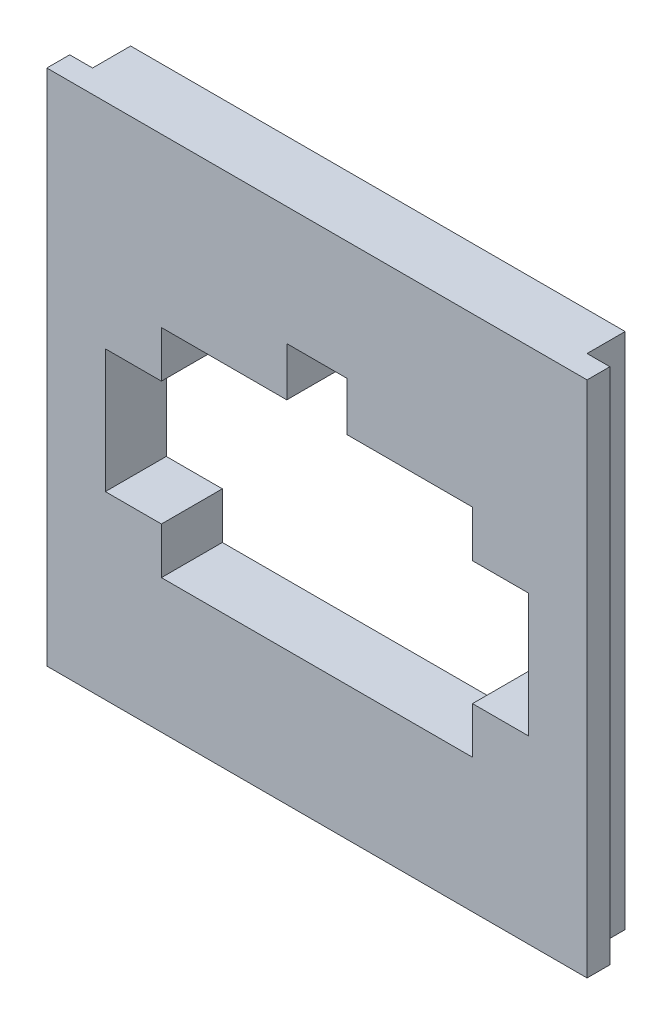
SolidWorks part; units mm, degrees
material "PET"
ref_plane "Front Plane" through (0, 0, 0) normal (0, 0, 1) x (1, 0, 0)
ref_plane "Top Plane" through (0, 0, 0) normal (0, 1, 0) x (1, 0, 0)
ref_plane "Right Plane" through (0, 0, 0) normal (1, 0, 0) x (0, 0, -1)
sketch "Sketch1" plane through (0, 0, 0) normal (0, 0, 1) x (1, 0, 0)
  line L1 (-5.7029, 6.1497) -> (10.5271, 6.1497)
  line L2 (-5.7029, 6.1497) -> (-5.7029, -10.8503)
  line L3 (-5.7029, -10.8503) -> (10.5271, -10.8503)
  line L4 (10.5271, 6.1497) -> (10.5271, -10.8503)
  dimension "D1" = 17
  dimension "D2" = 16.23
extrude "Boss-Extrude1" add sketch "Sketch1" along normal blind 2
sketch "Sketch2" plane through (10.5271, 0, 0) normal (1, 0, 0) x (0, 0, -1)
  line L0 (-2, -10.8503) -> (0, -10.8503) construction
  line L1 (-2, 6.1497) -> (-1.251, 6.1497)
  line L2 (-2, 6.1497) -> (-2, -10.8503)
  line L3 (-2, -10.8503) -> (-1.251, -10.8503)
  line L4 (-1.251, 6.1497) -> (-1.251, -10.8503)
  dimension "D1" = 0.749
extrude "Boss-Extrude2" add sketch "Sketch2" along normal blind 0.75
sketch "Sketch3" plane through (-5.7029, 0, 0) normal (-1, 0, 0) x (0, 0, 1)
  line L0 (2, -10.8503) -> (0, -10.8503) construction
  line L1 (2, 6.1497) -> (1.25, 6.1497)
  line L2 (2, 6.1497) -> (2, -10.8503)
  line L3 (2, -10.8503) -> (1.25, -10.8503)
  line L4 (1.25, 6.1497) -> (1.25, -10.8503)
  dimension "D1" = 0.75
extrude "Boss-Extrude4" add sketch "Sketch3" along normal blind 0.75
sketch "Sketch4" plane through (0, 0, 0) normal (0, 0, -1) x (-1, 0, 0)
  line L0 (-2.4121, 6.1497) -> (-2.4121, -10.8503) construction
  line L1 (-10.5271, 6.1497) -> (5.7029, 6.1497) construction
  line L2 (5.7029, -10.8503) -> (-10.5271, -10.8503) construction
  line L3 (-10.5271, -2.3503) -> (5.7029, -2.3503) construction
  line L4 (-10.5271, -10.8503) -> (-10.5271, 6.1497) construction
  line L5 (5.7029, 6.1497) -> (5.7029, -10.8503) construction
  line L6 (-7.5171, 0.654) -> (-3.4021, 0.654)
  line L7 (-7.5171, -6.456) -> (2.6929, -6.456)
  line L8 (-3.4021, 2.254) -> (-1.4221, 2.254)
  line L9 (-3.4021, 2.254) -> (-3.4021, 0.654)
  line L10 (-1.4221, 2.254) -> (-1.4221, 0.654)
  line L11 (-1.4221, 0.654) -> (2.6929, 0.654)
  line L12 (2.6929, 0.654) -> (2.6929, -0.871)
  line L13 (2.6929, -0.871) -> (4.5329, -0.871)
  line L14 (2.6929, -4.931) -> (4.5329, -4.931)
  line L15 (4.5329, -0.871) -> (4.5329, -4.931)
  line L16 (-9.3571, -0.871) -> (-7.5171, -0.871)
  line L17 (-9.3571, -0.871) -> (-9.3571, -4.931)
  line L18 (-9.3571, -4.931) -> (-7.5171, -4.931)
  line L19 (2.6929, -6.456) -> (2.6929, -4.931)
  line L20 (-7.5171, -6.456) -> (-7.5171, -4.931)
  line L21 (-7.5171, 0.654) -> (-7.5171, -0.871)
  dimension "D1" = 4.06
  dimension "D2" = 10.21
  dimension "D3" = 13.89
  dimension "D4" = 1.98
  dimension "D5" = 8.71
  dimension "D6" = 7.11
extrude "Cut-Extrude1" cut sketch "Sketch4" against normal through all
sketch "Sketch6" plane through (0, 0, 0) normal (0, 0, -1) x (-1, 0, 0)
  line L0 (-2.4121, -6.456) -> (-2.4121, -10.8503) construction
  line L1 (-7.5171, -6.456) -> (2.6929, -6.456) construction
  line L2 (5.7029, -10.8503) -> (-10.5271, -10.8503) construction
  line L3 (-5.4121, -10.8503) -> (0.5879, -10.8503)
  arc A0 (-5.4121, -10.8503) -> (0.5879, -10.8503) centre (-2.4121, -10.8503) cw
extrude "Cut-Extrude3" cut sketch "Sketch6" against normal blind 0.5
